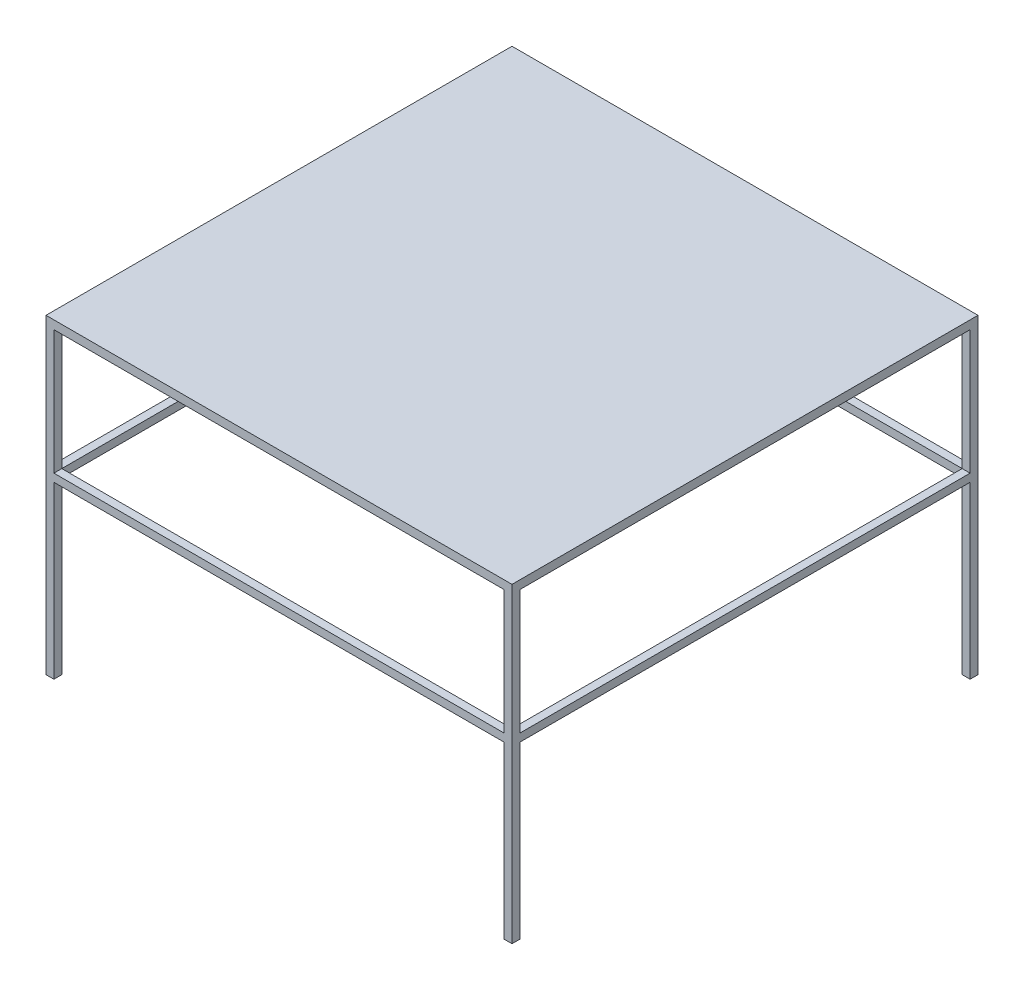
SolidWorks part; units mm, degrees
ref_plane "Alzado" through (0, 0, 0) normal (0, 0, 1) x (1, 0, 0)
ref_plane "Planta" through (0, 0, 0) normal (0, 1, 0) x (1, 0, 0)
ref_plane "Vista lateral" through (0, 0, 0) normal (1, 0, 0) x (0, 0, -1)
sketch "Croquis1" plane through (0, 0, 0) normal (0, 1, 0) x (1, 0, 0)
  line L0 (25.4, 0) -> (750, 0) construction
  line L1 (0, 0) -> (25.4, 0)
  line L2 (0, 0) -> (0, -25.4)
  line L3 (0, -25.4) -> (25.4, -25.4)
  line L4 (25.4, 0) -> (25.4, -25.4)
  line L5 (750, 0) -> (750, -750) construction
  line L6 (1474.6, 0) -> (1474.6, -25.4)
  line L7 (1500, -25.4) -> (1474.6, -25.4)
  line L8 (1500, 0) -> (1500, -25.4)
  line L9 (1500, 0) -> (1474.6, 0)
  line L10 (750, -750) -> (244.641, -750) construction
  line L11 (25.4, -1500) -> (750, -1500) construction
  line L12 (1500, -1500) -> (1474.6, -1500)
  line L13 (1500, -1500) -> (1500, -1474.6)
  line L14 (1500, -1474.6) -> (1474.6, -1474.6)
  line L15 (1474.6, -1500) -> (1474.6, -1474.6)
  line L16 (25.4, -1500) -> (25.4, -1474.6)
  line L17 (0, -1474.6) -> (25.4, -1474.6)
  line L18 (0, -1500) -> (0, -1474.6)
  line L19 (0, -1500) -> (25.4, -1500)
  dimension "D1" = 25.4
  dimension "D2" = 25.4
  dimension "D3" = 750
  dimension "D4" = 750
extrude "Saliente-Extruir1" add sketch "Croquis1" along normal blind 1000
sketch "Croquis3" plane through (0, 0, 1500) normal (0, 0, 1) x (1, 0, 0)
  line L0 (1474.6, 1000) -> (1474.6, 0) construction
  line L1 (25.4, 1000) -> (1474.6, 1000)
  line L2 (25.4, 1000) -> (25.4, 974.6)
  line L3 (25.4, 974.6) -> (1474.6, 974.6)
  line L4 (1474.6, 1000) -> (1474.6, 974.6)
  line L5 (25.4, 1000) -> (25.4, 0) construction
  line L6 (25.4, 574.6) -> (1474.6, 574.6)
  line L7 (25.4, 574.6) -> (25.4, 549.2)
  line L8 (25.4, 549.2) -> (1474.6, 549.2)
  line L9 (1474.6, 574.6) -> (1474.6, 549.2)
  dimension "D1" = 25.4
  dimension "D2" = 25.4
  dimension "D3" = 400
extrude "Saliente-Extruir2" add sketch "Croquis3" against normal up to surface (25.4 mm away) up to face at (12.7, 500, 1474.6)
sketch "Croquis4" plane through (1500, 0, 0) normal (1, 0, 0) x (0, 0, -1)
  line L0 (-25.4, 1000) -> (-25.4, 0) construction
  line L1 (-1474.6, 1000) -> (-25.4, 1000)
  line L2 (-1474.6, 1000) -> (-1474.6, 974.6)
  line L3 (-1474.6, 974.6) -> (-25.4, 974.6)
  line L4 (-25.4, 1000) -> (-25.4, 974.6)
  line L6 (-1474.6, 574.6) -> (-25.4, 574.6)
  line L7 (-1474.6, 574.6) -> (-1474.6, 549.2)
  line L8 (-1474.6, 549.2) -> (-25.4, 549.2)
  line L9 (-25.4, 574.6) -> (-25.4, 549.2)
  dimension "D1" = 25.4
extrude "Saliente-Extruir3" add sketch "Croquis4" against normal blind 25.4
sketch "Croquis5" plane through (0, 0, 0) normal (0, 0, -1) x (-1, 0, 0)
  line L1 (-1474.6, 1000) -> (-25.4, 1000)
  line L2 (-1474.6, 1000) -> (-1474.6, 974.6)
  line L3 (-1474.6, 974.6) -> (-25.4, 974.6)
  line L4 (-25.4, 1000) -> (-25.4, 974.6)
  line L5 (-1474.6, 574.6) -> (-25.4, 574.6)
  line L6 (-1474.6, 574.6) -> (-1474.6, 549.2)
  line L7 (-1474.6, 549.2) -> (-25.4, 549.2)
  line L8 (-25.4, 574.6) -> (-25.4, 549.2)
extrude "Saliente-Extruir4" add sketch "Croquis5" against normal blind 25.4
sketch "Croquis6" plane through (0, 0, 0) normal (-1, 0, 0) x (0, 0, 1)
  line L1 (25.4, 1000) -> (1474.6, 1000)
  line L2 (25.4, 1000) -> (25.4, 974.6)
  line L3 (25.4, 974.6) -> (1474.6, 974.6)
  line L4 (1474.6, 1000) -> (1474.6, 974.6)
  line L5 (25.4, 574.6) -> (1474.6, 574.6)
  line L6 (25.4, 574.6) -> (25.4, 549.2)
  line L7 (25.4, 549.2) -> (1474.6, 549.2)
  line L8 (1474.6, 574.6) -> (1474.6, 549.2)
extrude "Saliente-Extruir5" add sketch "Croquis6" against normal blind 25.4
sketch "Croquis7" plane through (0, 1000, 0) normal (0, 1, 0) x (1, 0, 0)
  line L1 (1500, 0) -> (0, 0)
  line L2 (1500, 0) -> (1500, -1500)
  line L3 (1500, -1500) -> (0, -1500)
  line L4 (0, 0) -> (0, -1500)
extrude "Saliente-Extruir6" add sketch "Croquis7" along normal blind 1.9
